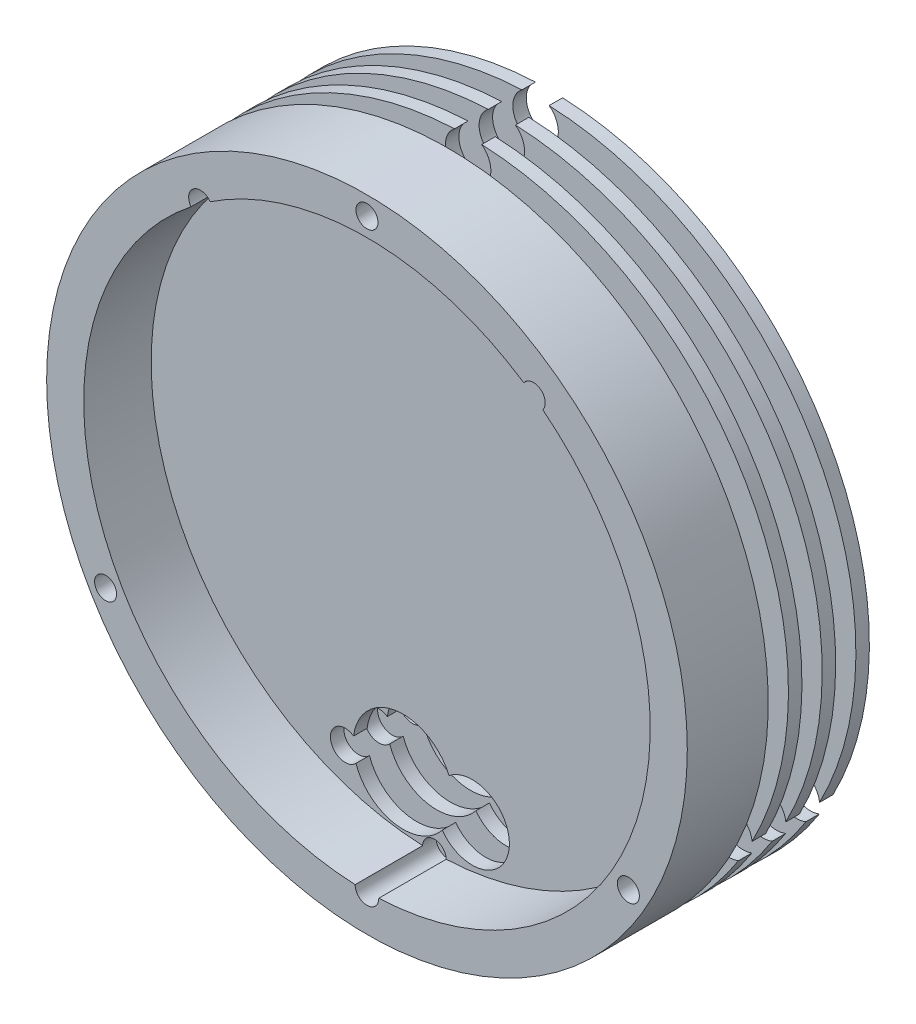
SolidWorks part; units mm, degrees
ref_plane "Plan de face" through (0, 0, 0) normal (0, 0, 1) x (1, 0, 0)
ref_plane "Plan de dessus" through (0, 0, 0) normal (0, 1, 0) x (1, 0, 0)
ref_plane "Plan de droite" through (0, 0, 0) normal (1, 0, 0) x (0, 0, -1)
sketch "Sketch1" plane through (0, 0, 0) normal (0, 0, 1) x (1, 0, 0)
  circle A0 centre (0, 0) radius 42
  circle A1 centre (0, 0) radius 47.5
extrude "Boss-Extrude1" add sketch "Sketch1" along normal blind 10
sketch "Sketch4" plane through (0, 0, 0) normal (0, 0, -1) x (-1, 0, 0)
  circle A0 centre (0, 0) radius 47.5
extrude "Boss-Extrude2" add sketch "Sketch4" along normal blind 20
sketch "Sketch5" plane through (0, 0, -20) normal (0, 0, -1) x (-1, 0, 0)
  circle A0 centre (0, 0) radius 47.5
  circle A1 centre (0, 0) radius 26
extrude "Cut-Extrude1" cut sketch "Sketch5" against normal blind 3
pattern_linear "LPattern1" count 4 spacing 5 along (0, 0, 1) of "Cut-Extrude1"
sketch "Sketch13" plane through (0, 0, -17) normal (0, 0, -1) x (-1, 0, 0)
  line L0 (0, 47.5) -> (0, 42)
  circle A0 centre (0, 0) radius 47.5 construction
hole_wizard "CBORE for #4 Binding Head Machine Screw3" positions "Sketch14" profile "Sketch15" counterbore size "#4" standard "ANSI Inch" end condition through all
sketch "Sketch14" plane through (0, 0, -17) normal (0, 0, -1) x (-1, 0, 0)
  line L0 (0, 47.5) -> (0, 42) construction
  point P0 (0, 44.75)
sketch "Sketch15" plane through (0, 44.75, -17) normal (1, 0, 0) x (0, 1, 0)
  line L0 (0, 0) -> (0, 27)
  line L1 (0, 27) -> (1.6319, 27)
  line L3 (1.6319, 27) -> (1.6319, 14.4272)
  line L4 (1.6319, 14.4272) -> (3.3731, 14.4272)
  line L5 (3.3731, 14.4272) -> (3.3731, 0)
  line L7 (3.3731, 0) -> (0, 0)
  line L11 (0, -6.35) -> (0, 107.95) construction
  dimension "Thru Hole Dia." = 3.2639
  dimension "Thru Hole Depth" = 27
  dimension "C'Bore Dia." = 6.7462
  dimension "C'Bore Depth" = 14.4272
pattern_circular "CirPattern2" count 3 over 360 about axis through (0, 0, 0) along (0, 0, 1) of "CBORE for #4 Binding Head Machine Screw3"
sketch "Sketch16" plane through (0, 0, 10) normal (0, 0, 1) x (1, 0, 0)
  circle A0 centre (0, -42) radius 1.75
  circle A1 centre (0, 0) radius 42 construction
extrude "Cut-Extrude2" cut sketch "Sketch16" against normal blind 12 contours A0
pattern_circular "CirPattern3" count 5 over 360 about axis through (0, 0, 10) along (0, 0, -1) skipping 1, 4 of "Cut-Extrude2"
sketch "Sketch21" plane through (0, 0, -20) normal (0, 0, -1) x (-1, 0, 0)
  circle A0 centre (-13.4343, 32.7769) radius 6
extrude "Cut-Extrude5" cut sketch "Sketch21" against normal blind 20
sketch "Sketch22" plane through (0, 0, -20) normal (0, 0, -1) x (-1, 0, 0)
  circle A0 centre (4.637, -33.9178) radius 7.4
extrude "Cut-Extrude6" cut sketch "Sketch22" against normal blind 22
sketch "Sketch23" plane through (0, 0, -20) normal (0, 0, -1) x (-1, 0, 0)
  circle A0 centre (-5.615, -35.295) radius 5.5
extrude "Cut-Extrude7" cut sketch "Sketch23" against normal blind 22
sketch "Sketch24" plane through (0, 0, -20) normal (0, 0, -1) x (-1, 0, 0)
  circle A0 centre (13.2268, -34.8201) radius 2.2
extrude "Cut-Extrude8" cut sketch "Sketch24" against normal blind 22
